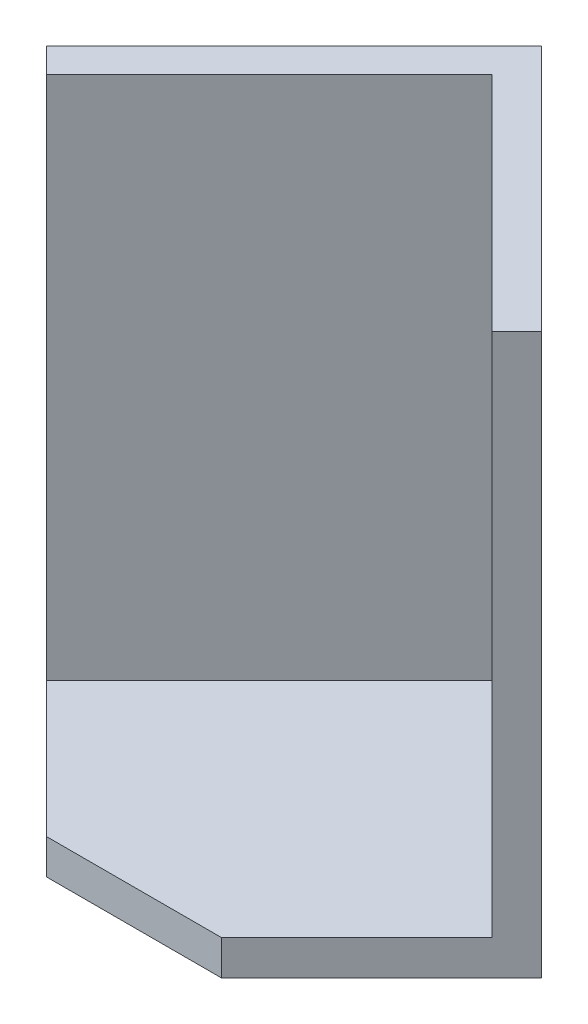
SolidWorks part; units mm, degrees
ref_plane "Front Plane" through (0, 0, 0) normal (0, 0, 1) x (1, 0, 0)
ref_plane "Top Plane" through (0, 0, 0) normal (0, 1, 0) x (1, 0, 0)
ref_plane "Right Plane" through (0, 0, 0) normal (1, 0, 0) x (0, 0, -1)
sketch "Sketch1" plane through (0, 0, 0) normal (0, 1, 0) x (1, 0, 0)
  line L0 (0, -40.0823) -> (70.7107, -110.7929) construction
  line L1 (0, -40.0823) -> (-70.7107, -110.7929) construction
  line L2 (0, -40.0823) -> (70.7107, -110.7929)
  line L3 (0, -40.0823) -> (-70.7107, -110.7929)
  line L4 (0, -54.2244) -> (63.6396, -117.864)
  line L5 (0, -54.2244) -> (-63.6396, -117.864)
  line L6 (70.7107, -110.7929) -> (63.6396, -117.864)
  line L7 (-70.7107, -110.7929) -> (-63.6396, -117.864)
  dimension "D1" = 10
extrude "Boss-Extrude1" add sketch "Sketch1" along normal mid plane 160
sketch "Sketch2" plane through (0, -80, 0) normal (0, -1, 0) x (1, 0, 0)
  line L0 (-63.6396, 117.864) -> (0, 54.2244)
  line L1 (-63.6396, 117.864) -> (-25, 156.5036)
  line L2 (0, 54.2244) -> (63.6396, 117.864)
  line L3 (25, 156.5036) -> (63.6396, 117.864)
  line L4 (-25, 156.5036) -> (25, 156.5036)
  line L5 (63.6396, 117.864) -> (70.7107, 110.7929) construction
  point P8 (63.6396, 117.864)
  dimension "D1" = 50
extrude "Boss-Extrude2" add sketch "Sketch2" against normal blind 10
